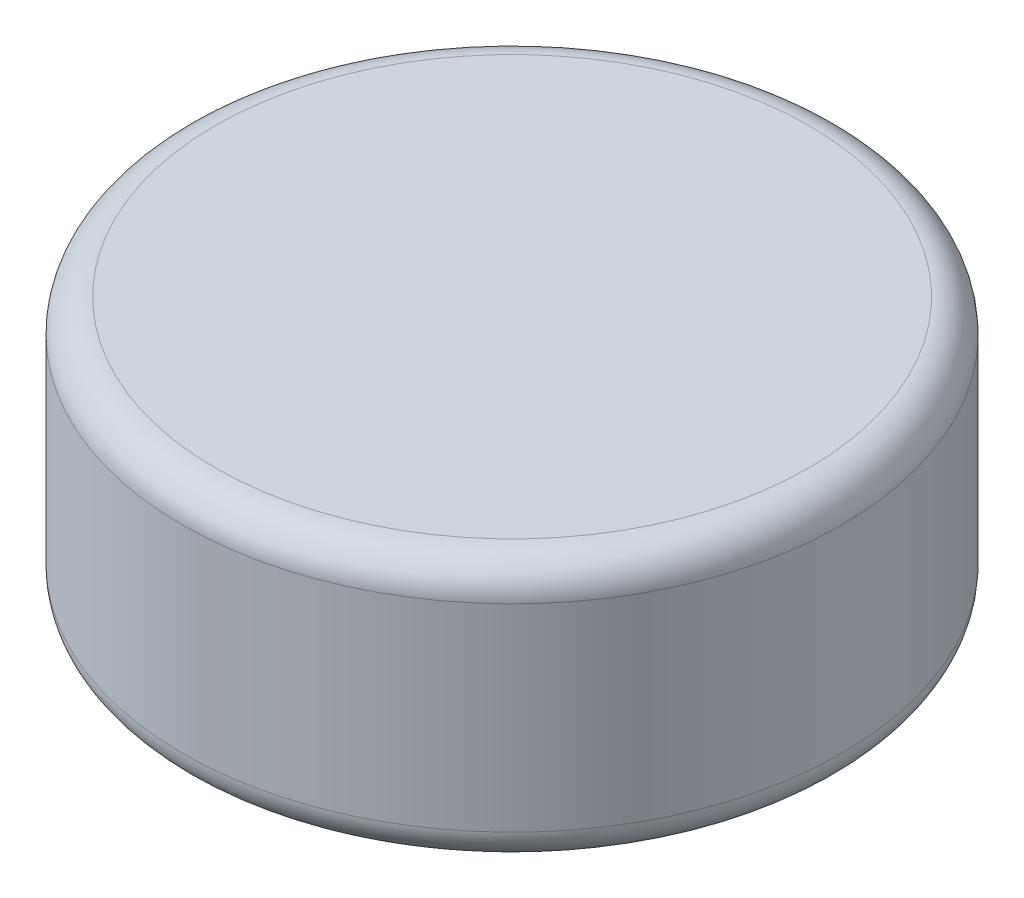
SolidWorks part; units mm, degrees
ref_plane "Front Plane" through (0, 0, 0) normal (0, 0, 1) x (1, 0, 0)
ref_plane "Top Plane" through (0, 0, 0) normal (0, 1, 0) x (1, 0, 0)
ref_plane "Right Plane" through (0, 0, 0) normal (1, 0, 0) x (0, 0, -1)
sketch "Sketch1" plane through (0, 0, 0) normal (0, 1, 0) x (1, 0, 0)
  circle A0 centre (0, 0) radius 2.5
  dimension "D1" = 5
extrude "Boss-Extrude1" add sketch "Sketch1" along normal blind 2
fillet "Fillet1" radius 0.25 2 edges at (0, 0, 2.5) (0, 2, 2.5)
